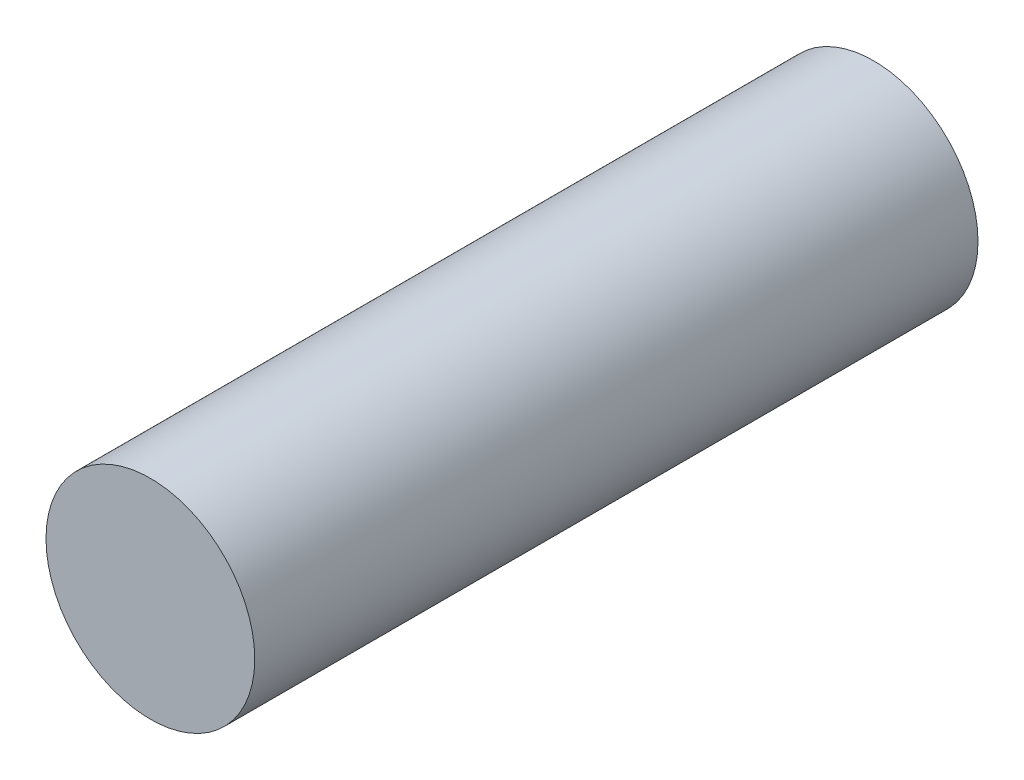
SolidWorks part; units mm, degrees
material "AISI 1020 Steel, Cold Rolled"
ref_plane "Front Plane" through (0, 0, 0) normal (0, 0, 1) x (1, 0, 0)
ref_plane "Top Plane" through (0, 0, 0) normal (0, 1, 0) x (1, 0, 0)
ref_plane "Right Plane" through (0, 0, 0) normal (1, 0, 0) x (0, 0, -1)
sketch "Sketch1" plane through (0, 0, 0) normal (0, 0, 1) x (1, 0, 0)
  circle A0 centre (0, 0) radius 6.35
  dimension "D1" = 12.7
extrude "Boss-Extrude1" add sketch "Sketch1" along normal blind 44
